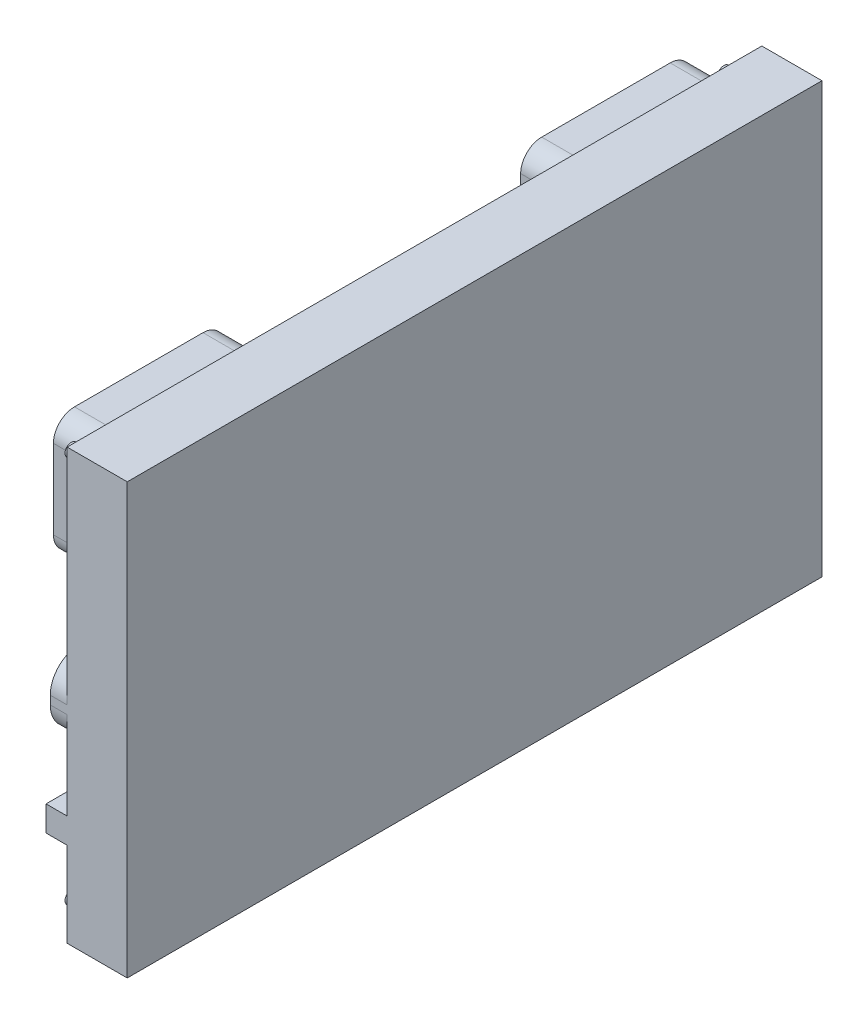
SolidWorks part; units mm, degrees
ref_plane "Alzado" through (0, 0, 0) normal (0, 0, 1) x (1, 0, 0)
ref_plane "Planta" through (0, 0, 0) normal (0, 1, 0) x (1, 0, 0)
ref_plane "Vista lateral" through (0, 0, 0) normal (1, 0, 0) x (0, 0, -1)
sketch "Croquis1" plane through (0, 0, 0) normal (1, 0, 0) x (0, 0, -1)
  line L1 (-72.204, 43.1537) -> (92.696, 43.1537)
  line L2 (-72.204, 43.1537) -> (-72.204, -58.8463)
  line L3 (-72.204, -58.8463) -> (92.696, -58.8463)
  line L4 (92.696, 43.1537) -> (92.696, -58.8463)
  dimension "D1" = 164.9
  dimension "D2" = 102
extrude "Saliente-Extruir1" add sketch "Croquis1" along normal blind 14.27
sketch "Croquis2" plane through (0, 0, 0) normal (-1, 0, 0) x (0, 0, 1)
  line L0 (-92.696, -58.8463) -> (-92.696, 43.1537) construction
  line L1 (-81.696, -5.8463) -> (-92.696, -5.8463)
  line L2 (-81.696, -5.8463) -> (-81.696, 9.1537)
  line L3 (-81.696, 9.1537) -> (-92.696, 9.1537)
  line L4 (-92.696, -5.8463) -> (-92.696, 9.1537)
  line L5 (-81.696, -5.8463) -> (-92.696, 9.1537) construction
  line L6 (-81.696, 9.1537) -> (-92.696, -5.8463) construction
  line L7 (-92.696, 43.1537) -> (72.204, 43.1537) construction
  point P0 (-87.196, 1.6537)
  dimension "D1" = 41.5
  dimension "D2" = 15
  dimension "D3" = 11
extrude "Saliente-Extruir3" add sketch "Croquis2" along normal blind 6
sketch "Croquis3" plane through (0, 0, 0) normal (-1, 0, 0) x (0, 0, 1)
  line L0 (-92.696, -58.8463) -> (-92.696, -5.8463) construction
  line L6 (-86.696, -40.3463) -> (-92.696, -40.3463)
  line L7 (72.204, -58.8463) -> (-92.696, -58.8463) construction
  line L8 (-86.696, -22.3463) -> (-92.696, -22.3463)
  line L9 (-86.696, -22.3463) -> (-86.696, -15.3463)
  line L10 (-86.696, -15.3463) -> (-92.696, -15.3463)
  line L11 (-92.696, -22.3463) -> (-92.696, -15.3463)
  line L12 (-86.696, -22.3463) -> (-92.696, -15.3463) construction
  line L13 (-86.696, -15.3463) -> (-92.696, -22.3463) construction
  line L14 (-86.696, -40.3463) -> (-86.696, -33.3463)
  line L15 (-86.696, -33.3463) -> (-92.696, -33.3463)
  line L16 (-92.696, -40.3463) -> (-92.696, -33.3463)
  line L17 (-86.696, -40.3463) -> (-92.696, -33.3463) construction
  line L18 (-86.696, -33.3463) -> (-92.696, -40.3463) construction
  point P0 (-87.0305, -36.8463)
  point P1 (-89.696, -36.8463)
  point P7 (-89.696, -18.8463)
  dimension "D1" = 7
  dimension "D2" = 40
  dimension "D3" = 6
  dimension "D4" = 7
  dimension "D5" = 6
  dimension "D6" = 22
extrude "Saliente-Extruir4" add sketch "Croquis3" along normal blind 3
sketch "Croquis4" plane through (0, 0, 0) normal (-1, 0, 0) x (0, 0, 1)
  line L0 (72.204, 43.1537) -> (72.204, -58.8463) construction
  line L1 (57.204, -32.6863) -> (72.204, -32.6863)
  line L2 (57.204, -32.6863) -> (57.204, -38.6863)
  line L3 (57.204, -38.6863) -> (72.204, -38.6863)
  line L4 (72.204, -32.6863) -> (72.204, -38.6863)
  line L5 (57.204, -32.6863) -> (72.204, -38.6863) construction
  line L6 (57.204, -38.6863) -> (72.204, -32.6863) construction
  line L7 (72.204, -58.8463) -> (-92.696, -58.8463) construction
  point P0 (64.704, -35.6863)
  dimension "D1" = 15
  dimension "D2" = 6
  dimension "D3" = 23.16
extrude "Saliente-Extruir5" add sketch "Croquis4" along normal blind 5
sketch "Croquis5" plane through (0, 0, 0) normal (-1, 0, 0) x (0, 0, 1)
  line L0 (72.204, -58.8463) -> (-92.696, -58.8463) construction
  line L1 (-80.946, 40.5537) -> (-50.446, 40.5537)
  line L2 (-85.946, 35.5537) -> (-85.946, 16.7537)
  line L3 (-80.946, 11.7537) -> (-50.446, 11.7537)
  line L4 (-45.446, 35.5537) -> (-45.446, 16.7537)
  line L5 (-85.946, 40.5537) -> (-45.446, 11.7537) construction
  line L6 (-85.946, 11.7537) -> (-45.446, 40.5537) construction
  line L7 (29.954, 40.5537) -> (60.454, 40.5537)
  line L8 (24.954, 35.5537) -> (24.954, 16.7537)
  line L9 (29.954, 11.7537) -> (60.454, 11.7537)
  line L10 (65.454, 35.5537) -> (65.454, 16.7537)
  line L11 (24.954, 40.5537) -> (65.454, 11.7537) construction
  line L12 (24.954, 11.7537) -> (65.454, 40.5537) construction
  line L13 (-92.696, 9.1537) -> (-92.696, 43.1537) construction
  line L14 (72.204, 43.1537) -> (72.204, -32.6863) construction
  arc A0 (60.454, 11.7537) -> (65.454, 16.7537) centre (60.454, 16.7537) ccw
  arc A1 (60.454, 40.5537) -> (65.454, 35.5537) centre (60.454, 35.5537) cw
  arc A2 (29.954, 11.7537) -> (24.954, 16.7537) centre (29.954, 16.7537) cw
  arc A3 (29.954, 40.5537) -> (24.954, 35.5537) centre (29.954, 35.5537) ccw
  arc A4 (-45.446, 16.7537) -> (-50.446, 11.7537) centre (-50.446, 16.7537) cw
  arc A5 (-80.946, 11.7537) -> (-85.946, 16.7537) centre (-80.946, 16.7537) cw
  arc A6 (-85.946, 35.5537) -> (-80.946, 40.5537) centre (-80.946, 35.5537) cw
  arc A7 (-50.446, 40.5537) -> (-45.446, 35.5537) centre (-50.446, 35.5537) cw
  point P0 (-65.696, 26.1537)
  point P5 (45.204, 26.1537)
  dimension "D9" = 5
  dimension "D1" = 85
  dimension "D2" = 40.5
  dimension "D3" = 28.8
  dimension "D4" = 27
  dimension "D5" = 40.5
  dimension "D6" = 28.8
  dimension "D7" = 85
  dimension "D8" = 27
extrude "Saliente-Extruir6" add sketch "Croquis5" along normal blind 10
sketch "Croquis6" plane through (0, 0, 0) normal (-1, 0, 0) x (0, 0, 1)
  line L0 (72.204, 43.1537) -> (72.204, -32.6863) construction
  line L1 (58.204, -2.8463) -> (65.204, -2.8463)
  line L2 (58.204, -2.8463) -> (58.204, -18.8463)
  line L3 (58.204, -18.8463) -> (65.204, -18.8463)
  line L4 (72.204, -9.8463) -> (72.204, -11.8463)
  line L5 (58.204, -2.8463) -> (72.204, -18.8463) construction
  line L6 (58.204, -18.8463) -> (72.204, -2.8463) construction
  line L7 (72.204, -58.8463) -> (-92.696, -58.8463) construction
  arc A0 (72.204, -9.8463) -> (65.204, -2.8463) centre (65.204, -9.8463) ccw
  arc A1 (72.204, -11.8463) -> (65.204, -18.8463) centre (65.204, -11.8463) cw
  point P0 (65.204, -10.8463)
  dimension "D4" = 7
  dimension "D1" = 48
  dimension "D2" = 16
  dimension "D3" = 14
extrude "Saliente-Extruir7" add sketch "Croquis6" along normal blind 4
sketch "Croquis7" plane through (0, 0, 0) normal (-1, 0, 0) x (0, 0, 1)
  line L0 (-92.696, 9.1537) -> (-92.696, 43.1537) construction
  line L1 (-92.696, 43.1537) -> (72.204, 43.1537) construction
  line L2 (72.204, 43.1537) -> (72.204, -9.8463) construction
  line L3 (72.204, -58.8463) -> (-92.696, -58.8463) construction
  line L4 (-92.696, -58.8463) -> (-92.696, -40.3463) construction
  line L5 (72.204, -38.6863) -> (72.204, -58.8463) construction
  circle A0 centre (-87.691, 38.1537) radius 1.5
  circle A1 centre (67.204, 38.1537) radius 1.5
  circle A2 centre (-87.696, -53.8463) radius 1.5
  circle A3 centre (67.204, -53.8463) radius 1.5
  dimension "D1" = 3
  dimension "D4" = 5
  dimension "D6" = 3
  dimension "D9" = 3
  dimension "D2" = 5.005
  dimension "D3" = 5
  dimension "D5" = 5
  dimension "D7" = 5
  dimension "D8" = 5
  dimension "D10" = 5
  dimension "D11" = 5
extrude "Saliente-Extruir8" add sketch "Croquis7" along normal blind 4
